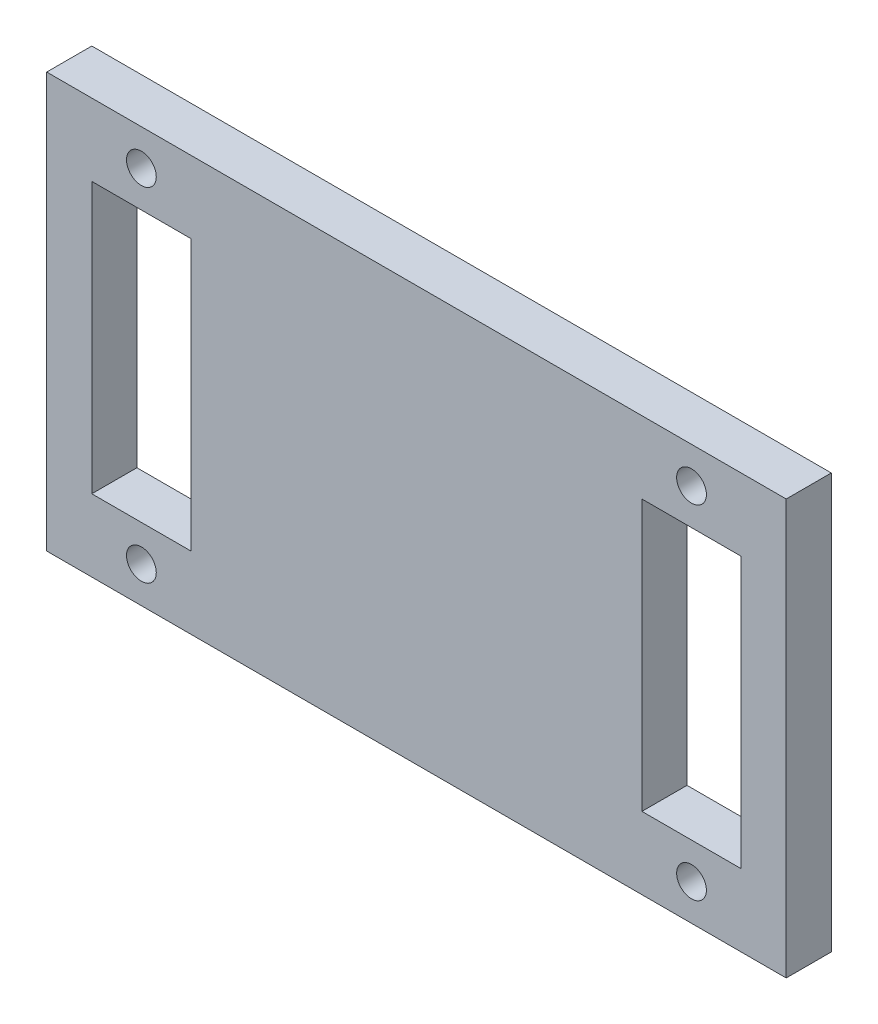
SolidWorks part; units mm, degrees
ref_plane "Plan de face" through (0, 0, 0) normal (0, 0, 1) x (1, 0, 0)
ref_plane "Plan de dessus" through (0, 0, 0) normal (0, 1, 0) x (1, 0, 0)
ref_plane "Plan de droite" through (0, 0, 0) normal (1, 0, 0) x (0, 0, -1)
sketch "Esquisse1" plane through (0, 0, 0) normal (0, 0, 1) x (1, 0, 0)
  line L0 (-16, 36.911) -> (-5, 36.911) construction
  line L1 (-82, 82.911) -> (0, 82.911)
  line L2 (-82, 82.911) -> (-82, 36.911)
  line L3 (-82, 36.911) -> (0, 36.911)
  line L4 (0, 82.911) -> (0, 36.911)
  line L5 (-66, 44.911) -> (-77, 44.911)
  line L6 (-66, 44.911) -> (-66, 74.911)
  line L7 (-66, 74.911) -> (-77, 74.911)
  line L8 (-77, 44.911) -> (-77, 74.911)
  line L9 (-16, 44.911) -> (-5, 44.911)
  line L10 (-16, 44.911) -> (-16, 74.911)
  line L11 (-16, 74.911) -> (-5, 74.911)
  line L12 (-5, 44.911) -> (-5, 74.911)
  circle A0 centre (-10.5, 40.911) radius 1.65
  circle A1 centre (-10.5, 78.911) radius 1.65
  circle A2 centre (-71.5, 40.911) radius 1.65
  circle A3 centre (-71.5, 78.911) radius 1.65
  dimension "D1" = 46
  dimension "D2" = 5
extrude "Boss.-Extru.1" add sketch "Esquisse1" along normal blind 5
